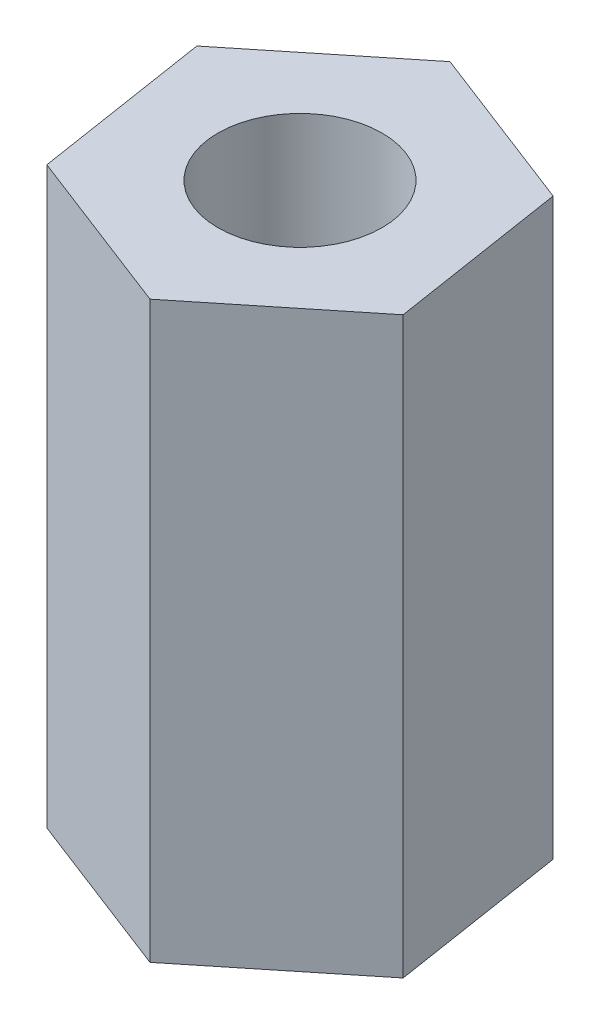
SolidWorks part; units mm, degrees
ref_plane "Front Plane" through (0, 0, 0) normal (0, 0, 1) x (1, 0, 0)
ref_plane "Top Plane" through (0, 0, 0) normal (0, 1, 0) x (1, 0, 0)
ref_plane "Right Plane" through (0, 0, 0) normal (1, 0, 0) x (0, 0, -1)
sketch "Szkic1" plane through (0, 0, 0) normal (0, 1, 0) x (1, 0, 0)
  line L1 (-10.2338, 3.9499) -> (-8.5376, -6.8878)
  line L2 (-8.5376, -6.8878) -> (1.6962, -10.8377)
  line L3 (1.6962, -10.8377) -> (10.2338, -3.9499)
  line L4 (10.2338, -3.9499) -> (8.5376, 6.8878)
  line L5 (8.5376, 6.8878) -> (-1.6962, 10.8377)
  line L6 (-1.6962, 10.8377) -> (-10.2338, 3.9499)
  circle A0 centre (0, 0) radius 9.5 construction
  circle A1 centre (0, 0) radius 5
  dimension "D2" = 10
  dimension "D1" = 19
extrude "Dodanie-wyciągnięcie1" add sketch "Szkic1" along normal blind 35
